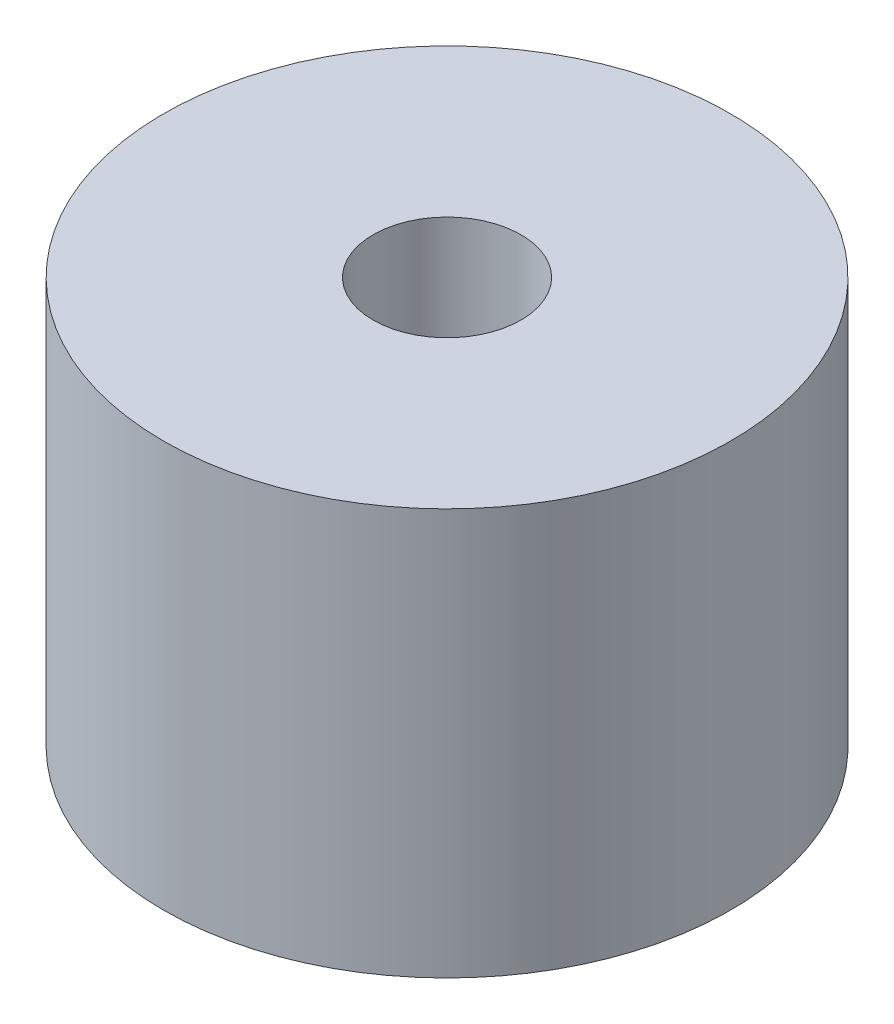
SolidWorks part; units mm, degrees
ref_plane "Front Plane" through (0, 0, 0) normal (0, 0, 1) x (1, 0, 0)
ref_plane "Top Plane" through (0, 0, 0) normal (0, 1, 0) x (1, 0, 0)
ref_plane "Right Plane" through (0, 0, 0) normal (1, 0, 0) x (0, 0, -1)
sketch "Sketch1" plane through (0, 0, 0) normal (0, 1, 0) x (1, 0, 0)
  circle A0 centre (0, 0) radius 5.75
  circle A1 centre (0, 0) radius 1.5
  dimension "D1" = 11.5
  dimension "D2" = 3
extrude "Boss-Extrude1" add sketch "Sketch1" along normal blind 8.24
